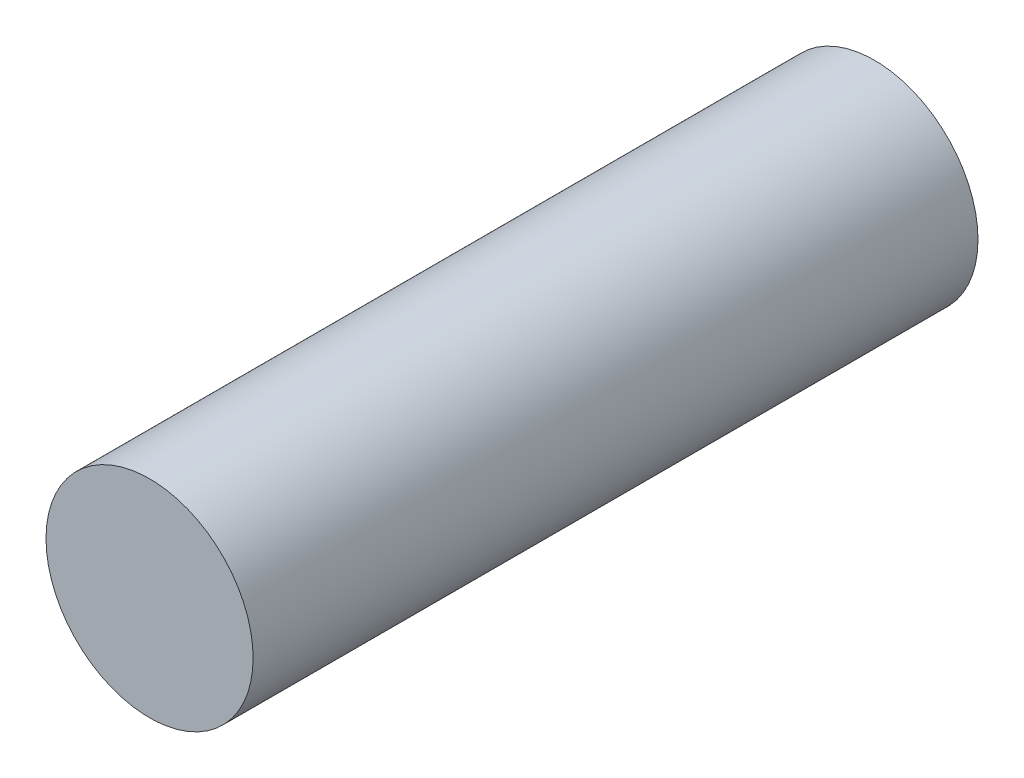
SolidWorks part; units mm, degrees
ref_plane "前视基准面" through (0, 0, 0) normal (0, 0, 1) x (1, 0, 0)
ref_plane "上视基准面" through (0, 0, 0) normal (0, 1, 0) x (1, 0, 0)
ref_plane "右视基准面" through (0, 0, 0) normal (1, 0, 0) x (0, 0, -1)
other "Configuration Table"
sketch "草图1" plane through (0, 0, 0) normal (0, 0, 1) x (1, 0, 0)
  circle A0 centre (0, 0) radius 1
extrude "凸台-拉伸1" add sketch "草图1" along normal blind 7
